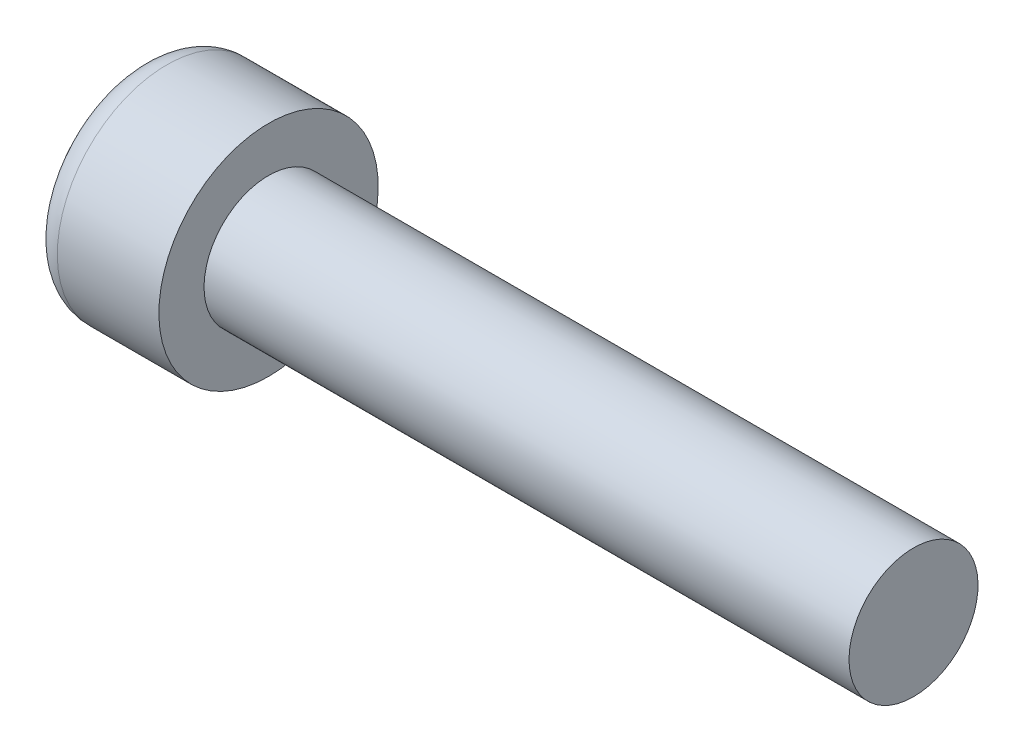
SolidWorks part; units mm, degrees
material "Plain Carbon Steel"
ref_plane "Front Plane" through (0, 0, 0) normal (0, 0, 1) x (1, 0, 0)
ref_plane "Top Plane" through (0, 0, 0) normal (0, 1, 0) x (1, 0, 0)
ref_plane "Right Plane" through (0, 0, 0) normal (1, 0, 0) x (0, 0, -1)
sketch "Sketch1" plane through (0, 0, 0) normal (0, 0, 1) x (1, 0, 0)
  line L0 (0, 0) -> (0, 3.1875)
  line L1 (1.0625, 4.25) -> (5, 4.25)
  line L2 (5, 4.25) -> (5, 2.5)
  line L3 (5, 2.5) -> (30, 2.5)
  line L4 (30, 2.5) -> (30, 0)
  line L5 (30, 0) -> (0, 0) construction
  line L6 (1.0625, 3.1875) -> (1.0625, 2.125) construction
  line L7 (1.0625, 2.125) -> (1.0625, 1.0625) construction
  line L8 (1.0625, 1.0625) -> (1.0625, 0) construction
  line L9 (1.0625, 4.25) -> (1.0625, 3.1875) construction
  line L10 (0, 0) -> (30, 0)
  arc A0 (0, 3.1875) -> (1.0625, 4.25) centre (1.0625, 3.1875) cw
  dimension "D1" = 5
  dimension "D2" = 8.5
  dimension "D3" = 5
  dimension "D4" = 25
revolve "Revolve1" add sketch "Sketch1" angle 360 about L10
sketch "Sketch2" plane through (0, 0, 0) normal (-1, 0, 0) x (0, 0, 1)
  line L1 (0, 2.3094) -> (-2, 1.1547)
  line L2 (-2, 1.1547) -> (-2, -1.1547)
  line L3 (-2, -1.1547) -> (0, -2.3094)
  line L4 (0, -2.3094) -> (2, -1.1547)
  line L5 (2, -1.1547) -> (2, 1.1547)
  line L6 (2, 1.1547) -> (0, 2.3094)
  circle A0 centre (0, 0) radius 2 construction
  dimension "D1" = 4
extrude "Cut-Extrude1" cut sketch "Sketch2" against normal blind 2.5
